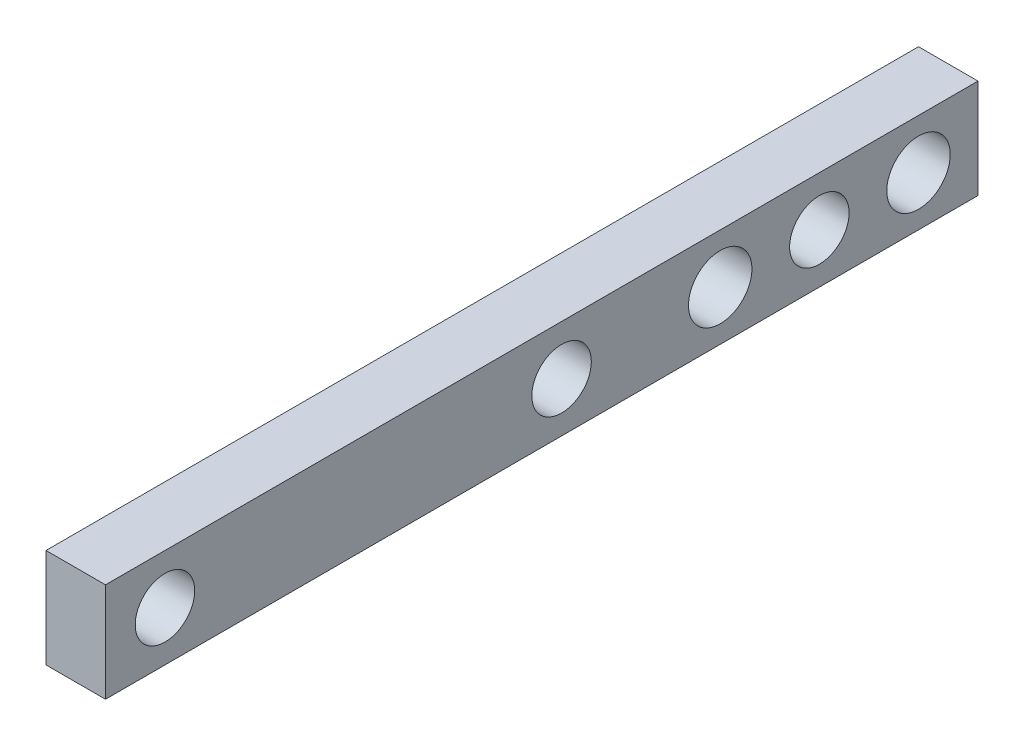
SolidWorks part; units mm, degrees
ref_plane "Front Plane" through (0, 0, 0) normal (0, 0, 1) x (1, 0, 0)
ref_plane "Top Plane" through (0, 0, 0) normal (0, 1, 0) x (1, 0, 0)
ref_plane "Right Plane" through (0, 0, 0) normal (1, 0, 0) x (0, 0, -1)
sketch "Sketch2" plane through (0, 0, 0) normal (1, 0, 0) x (0, 0, -1)
  line L1 (-22, -2.5) -> (22, -2.5)
  line L2 (-22, -2.5) -> (-22, 2.5)
  line L3 (-22, 2.5) -> (22, 2.5)
  line L4 (22, -2.5) -> (22, 2.5)
  line L5 (0, 2.5) -> (0, -2.5) construction
  line L6 (-22, 0) -> (22, 0) construction
  circle A0 centre (19, 0) radius 1.6
  circle A1 centre (9, 0) radius 1.6
  circle A2 centre (1, 0) radius 1.5
  circle A3 centre (-19, 0) radius 1.5
  point P0 (0, 0)
  dimension "D3" = 3.2
  dimension "D5" = 3.2
  dimension "D7" = 3
  dimension "D9" = 3
  dimension "D1" = 44
  dimension "D2" = 5
  dimension "D4" = 3
  dimension "D6" = 10
  dimension "D8" = 8
  dimension "D10" = 20
extrude "Boss-Extrude1" add sketch "Sketch2" along normal blind 3
sketch "Sketch3" plane through (3, 0, 0) normal (1, 0, 0) x (0, 0, -1)
  line L0 (-22, -2.5) -> (22, -2.5) construction
  circle A0 centre (14, 0) radius 1.5
  dimension "D1" = 3
  dimension "D2" = 5
  dimension "D3" = 2.5
extrude "Cut-Extrude1" cut sketch "Sketch3" against normal through all
